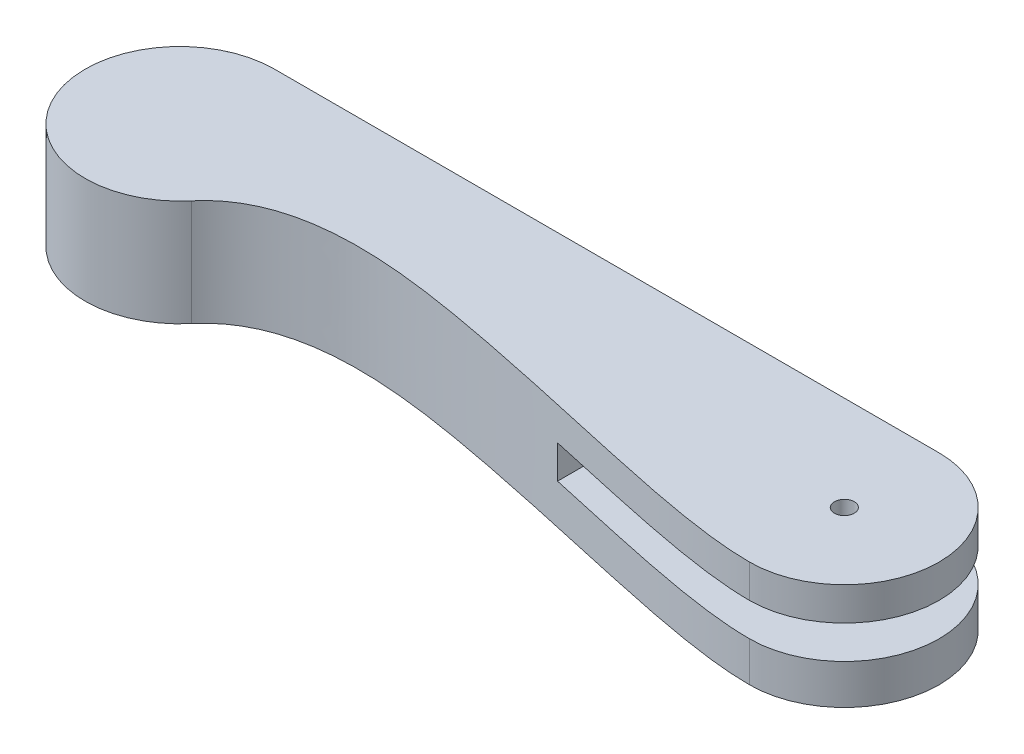
SolidWorks part; units mm, degrees
ref_plane "Front Plane" through (0, 0, 0) normal (0, 0, 1) x (1, 0, 0)
ref_plane "Top Plane" through (0, 0, 0) normal (0, 1, 0) x (1, 0, 0)
ref_plane "Right Plane" through (0, 0, 0) normal (1, 0, 0) x (0, 0, -1)
sketch "Sketch1" plane through (0, 0, 0) normal (0, 1, 0) x (1, 0, 0)
  line L0 (-50, 0) -> (50, 0) construction
  line L1 (-50, 14.25) -> (50, 14.25)
  line L2 (-50, -14.25) -> (50, -14.25)
  arc A0 (-50, 14.25) -> (-50, -14.25) centre (-50, 0) ccw
  arc A1 (50, -14.25) -> (50, 14.25) centre (50, 0) ccw
  point P3 (0, 0)
  dimension "D1" = 14.25
  dimension "D2" = 100
extrude "Boss-Extrude1" add sketch "Sketch1" along normal blind 6
sketch "Sketch2" plane through (0, 6, 0) normal (0, 1, 0) x (1, 0, 0)
  circle A0 centre (-50, 0) radius 8.25 construction
  circle A1 centre (-50, 8.25) radius 2.5
  circle A2 centre (-50, -8.25) radius 2.5
  point P9 (-50, 0)
  dimension "D1" = 16.5
  dimension "D2" = 5
  dimension "D3" = 2
extrude "Cut-Extrude1" cut sketch "Sketch2" against normal up to next
sketch "Sketch3" plane through (0, 0, 0) normal (0, -1, 0) x (1, 0, 0)
  circle A0 centre (50, 0) radius 1.5
  dimension "D1" = 3
extrude "Cut-Extrude2" cut sketch "Sketch3" against normal through all
sketch "Sketch4" plane through (0, 6, 0) normal (0, 1, 0) x (1, 0, 0)
  line L0 (-50, 14.25) -> (15, 14.25)
  line L1 (-50, 14.25) -> (50, 14.25) construction
  line L2 (15, 14.25) -> (15, -14.25)
  line L3 (-50, -14.25) -> (50, -14.25) construction
  line L4 (15, -14.25) -> (-50, -14.25)
  arc A0 (-50, 14.25) -> (-50, -14.25) centre (-50, 0) ccw
  arc A1 (-50, 14.25) -> (-50, -14.25) centre (-50, 0) ccw construction
  dimension "D1" = 65
extrude "Boss-Extrude2" add sketch "Sketch4" along normal blind 5
sketch "Sketch5" plane through (0, 11, 0) normal (0, 1, 0) x (1, 0, 0)
  line L0 (-50, 0) -> (50, 0) construction
  line L1 (-50, 14.25) -> (50, 14.25)
  line L2 (-50, -14.25) -> (50, -14.25)
  arc A0 (-50, 14.25) -> (-50, -14.25) centre (-50, 0) ccw
  arc A1 (50, -14.25) -> (50, 14.25) centre (50, 0) ccw
  point P4 (0, 0)
  dimension "D1" = 14.25
extrude "Boss-Extrude3" add sketch "Sketch5" along normal blind 5
sketch "Sketch6" plane through (0, 16, 0) normal (0, 1, 0) x (1, 0, 0)
  circle A0 centre (50, 0) radius 1.5
  dimension "D1" = 3
extrude "Cut-Extrude3" cut sketch "Sketch6" against normal up to next
sketch "Sketch7" plane through (0, 16, 0) normal (0, 1, 0) x (1, 0, 0)
  line L0 (0, -8.8) -> (0, 8.8) construction
  line L1 (-50, -14.25) -> (50, -14.25)
  circle A0 centre (-50, 0) radius 14.25
  circle A1 centre (50, 0) radius 14.25
  spline S0 degree 3 poles (-39.0732, -9.1469) (-31.5141, -0.117) (5.4387, -4.6452) (38.6975, -14.25) (50, -14.25) knots 0 0 0 0 0.435908 1 1 1 1
  line M5 (-50, -14.25) -> (50, -14.25)
extrude "Cut-Extrude4" cut sketch "Sketch7" against normal up to next contours S0 A0 M5
equation "\"Length\"= 100mm"
equation "\"Radius\"= 14.25mm"
equation "\"Thick\"= 6mm"
equation "\"D1@Sketch1\"= \"Radius\""
equation "\"D2@Sketch1\" = \"Length\""
equation "\"D1@Boss-Extrude1\"= \"Thick\""
equation "\"D1@Sketch4\"=\"Length\"*0.65"
equation "\"D1@Sketch5\"=\"Radius\""
